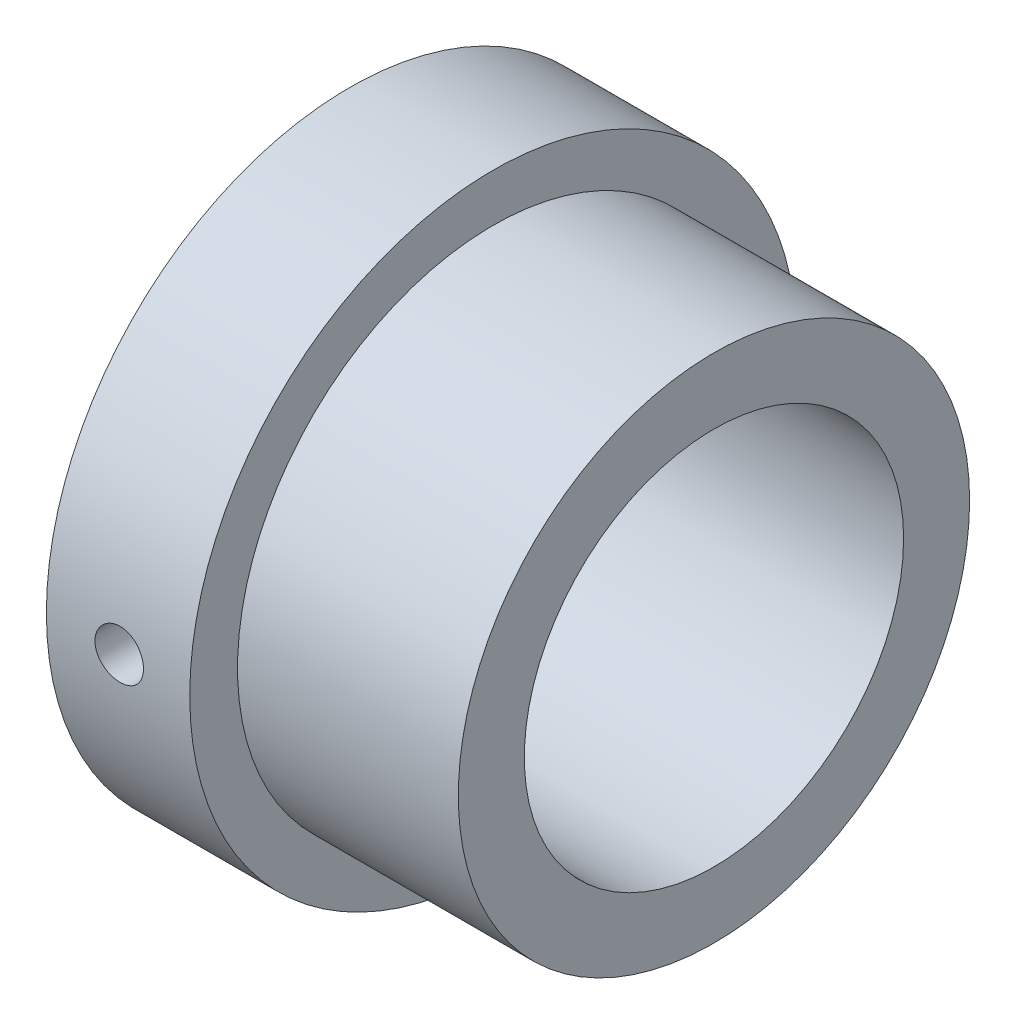
SolidWorks part; units mm, degrees
ref_plane "Front Plane" through (0, 0, 0) normal (0, 0, 1) x (1, 0, 0)
ref_plane "Top Plane" through (0, 0, 0) normal (0, 1, 0) x (1, 0, 0)
ref_plane "Right Plane" through (0, 0, 0) normal (1, 0, 0) x (0, 0, -1)
sketch "Sketch1" plane through (0, 0, 0) normal (1, 0, 0) x (0, 0, -1)
  circle A0 centre (0, 0) radius 6.35
  circle A1 centre (0, 0) radius 3.9688
  dimension "D1" = 7.9375
  dimension "D2" = 12.7
extrude "Boss-Extrude1" add sketch "Sketch1" along normal blind 7.62
sketch "Sketch2" plane through (0, 0, 0) normal (0, 0, 1) x (1, 0, 0)
  line L0 (7.62, 6.35) -> (0, 6.35) construction
  line L1 (3, 6.35) -> (7.62, 6.35)
  line L2 (3, 6.35) -> (3, 5.35)
  line L3 (3, 5.35) -> (7.62, 5.35)
  line L4 (7.62, 6.35) -> (7.62, 5.35)
  line L5 (0, 6.35) -> (0, -6.35) construction
  line L7 (7.62, -6.35) -> (7.62, 6.35) construction
  dimension "D1" = 3
  dimension "D2" = 0
  dimension "D3" = 1
ref_axis "Axis1" through (7.62, 0, 0) along (-1, 0, 0)
revolve "Cut-Revolve1" cut sketch "Sketch2" angle 360 about axis through (7.62, 0, 0) along (-1, 0, 0)
hole_wizard "#60 (0.04) Diameter Hole1" positions "Sketch4" profile "Sketch3" hole size "#60" standard "ANSI Inch"
sketch "Sketch4" plane through (0, 0, 0) normal (0, 0, 1) x (1, 0, 0)
  line L0 (7.62, 0) -> (0, 0) construction
  line L1 (0, 6.35) -> (0, -6.35) construction
  point P0 (1.524, 0)
  dimension "D1" = 1.524
sketch "Sketch3" plane through (1.524, 0, 0) normal (1, 0, 0) x (0, 1, 0)
  line L0 (0, 0) -> (0, 25.7052)
  line L1 (0, 25.7052) -> (0.508, 25.4)
  line L2 (0.508, 25.4) -> (0.508, 0)
  line L5 (0.508, 0) -> (0, 0)
  line L10 (0, 25.7052) -> (-0.508, 25.4) construction
  line L11 (0, -6.35) -> (0, 107.95) construction
  dimension "Hole Dia." = 1.016
  dimension "Hole Depth" = 25.4
  dimension "Drill Angle" = 118
ref_plane "Plane1" through (0, 0, -5.08) normal (0, 0, 1) x (1, 0, 0)
hole_wizard "1/32 (0.03125) Diameter Hole1" positions "Sketch6" profile "Sketch5" hole size "1/32" standard "ANSI Inch" end condition through all
sketch "Sketch6" plane through (0, 0, -5.08) normal (0, 0, 1) x (1, 0, 0)
  line L1 (0, 6.35) -> (0, -6.35) construction
  line L2 (7.62, 0) -> (0, 0) construction
  point P0 (1.524, -5.08)
  dimension "D1" = 1.524
  dimension "D2" = 5.08
sketch "Sketch5" plane through (1.524, -5.08, -5.08) normal (1, 0, 0) x (0, 1, 0)
  line L0 (0, 0) -> (0, 11.43)
  line L1 (0, 11.43) -> (0.3969, 11.43)
  line L2 (0.3969, 11.43) -> (0.3969, 0)
  line L5 (0.3969, 0) -> (0, 0)
  line L11 (0, -6.35) -> (0, 107.95) construction
  dimension "Thru Hole Dia." = 0.7937
  dimension "Thru Hole Depth" = 11.43
